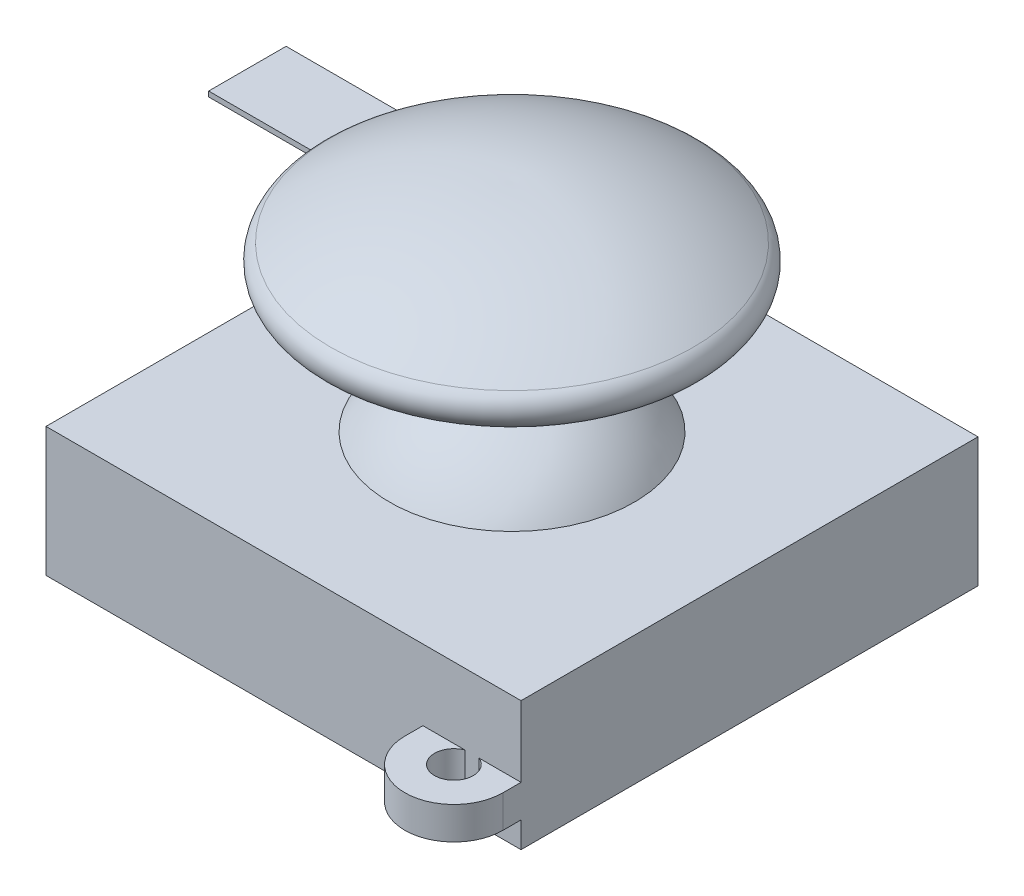
SolidWorks part; units mm, degrees
ref_plane "前视基准面" through (0, 0, 0) normal (0, 0, 1) x (1, 0, 0)
ref_plane "上视基准面" through (0, 0, 0) normal (0, 1, 0) x (1, 0, 0)
ref_plane "右视基准面" through (0, 0, 0) normal (1, 0, 0) x (0, 0, -1)
other "Configuration Table"
sketch "草图1" plane through (0, 0, 0) normal (0, 1, 0) x (1, 0, 0)
  line L1 (-9.2, -8.85) -> (9.2, -8.85)
  line L2 (-9.2, -8.85) -> (-9.2, 8.85)
  line L3 (-9.2, 8.85) -> (9.2, 8.85)
  line L4 (9.2, -8.85) -> (9.2, 8.85)
  line L5 (-9.2, -8.85) -> (9.2, 8.85) construction
  line L6 (-9.2, 8.85) -> (9.2, -8.85) construction
  point P0 (0, 0)
  dimension "D1" = 18.4
  dimension "D2" = 17.7
extrude "凸台-拉伸1" add sketch "草图1" along normal blind 5
ref_plane "基准面1" through (0, 1, 0) normal (0, -1, 0) x (-1, 0, 0)
sketch "草图2" plane through (0, 1, 0) normal (0, -1, 0) x (-1, 0, 0)
  line L0 (9.2, 8.85) -> (10.9, 8.85)
  line L1 (10.9, 5.05) -> (9.2, 5.05)
  line L2 (9.2, 8.85) -> (9.2, -8.85) construction
  line L3 (9.2, 5.05) -> (9.2, 8.85)
  line L4 (-9.2, -8.85) -> (-9.2, -9.55)
  line L5 (-5.4, -9.55) -> (-5.4, -8.85)
  line L6 (9.2, -8.85) -> (-9.2, -8.85) construction
  line L7 (-5.4, -8.85) -> (-7.0307, -8.85)
  line L8 (-14.0215, -11.45) -> (-1.3838, -11.45) construction
  line L9 (-9.2, 8.85) -> (9.2, 8.85) construction
  line L11 (12.8, 10.4378) -> (12.8, 1.7571) construction
  line L12 (-9.2, -8.85) -> (-9.2, 8.85) construction
  line L13 (-7.5693, -8.85) -> (-9.2, -8.85)
  arc A0 (10.9, 8.85) -> (10.9, 5.05) centre (10.9, 6.95) cw
  arc A1 (-9.2, -9.55) -> (-5.4, -9.55) centre (-7.3, -9.55) ccw
  arc A2 (-7.5693, -8.85) -> (-7.0307, -8.85) centre (-7.3, -9.55) ccw
  circle A3 centre (10.9, 6.95) radius 0.9
  dimension "D3" = 1.5
  dimension "D4" = 1.8
  dimension "D1" = 3.8
  dimension "D2" = 3.8
  dimension "D5" = 20.3
  dimension "D6" = 22
extrude "凸台-拉伸2" add sketch "草图2" against normal blind 1.26
ref_plane "基准面2" through (0, 0, 0) normal (1, 0, 0) x (0, 0, -1)
sketch "草图3" plane through (0, 0, 0) normal (1, 0, 0) x (0, 0, -1)
  line L0 (0, 0) -> (0, 7.6055) construction
  line L1 (4.74, 5) -> (0, 5)
  line L2 (-8.85, 5) -> (8.85, 5) construction
  line L3 (0, 7.6055) -> (0, 5)
  line L5 (6.6158, 10) -> (1.85, 10)
  line L6 (1.85, 10) -> (1.85, 7.2919)
  line L8 (0, 13.4) -> (0, 7.6055)
  line L9 (7.35, 14.4714) -> (7.35, 9.5201) construction
  line L10 (-4.6633, 13.4036) -> (3.8323, 13.4036) construction
  arc A0 (4.74, 5) -> (1.85, 7.2919) centre (0, 1.9912) ccw
  arc A1 (0, 13.4) -> (7.0268, 11.3425) centre (0.2946, 1.3781) cw
  arc A2 (7.0268, 11.3425) -> (6.6158, 10) centre (6.6158, 10.7342) cw
  dimension "D1" = 4.74
  dimension "D2" = 13.4
  dimension "D3" = 7.35
  dimension "D4" = 1.85
  dimension "D5" = 5
revolve "旋转1" add sketch "草图3" angle 360 about L8
ref_plane "基准面3" through (0, 0.2, 0) normal (0, -1, 0) x (-1, 0, 0)
sketch "草图4" plane through (0, 0.2, 0) normal (0, -1, 0) x (-1, 0, 0)
  line L0 (9.2, 8.85) -> (9.2, 9.2075)
  line L1 (10.1425, 10.15) -> (21.9, 10.15)
  line L2 (21.9, 10.15) -> (21.9, 13.15)
  line L3 (21.9, 13.15) -> (10.05, 13.15)
  line L4 (6.2, 9.3) -> (6.2, 8.85)
  line L5 (-9.2, 8.85) -> (9.2, 8.85) construction
  line L6 (6.2, 8.85) -> (9.2, 8.85)
  line L7 (9.2, -8.85) -> (-9.2, -8.85) construction
  arc A0 (9.2, 9.2075) -> (10.1425, 10.15) centre (10.1425, 9.2075) cw
  arc A1 (10.05, 13.15) -> (6.2, 9.3) centre (10.05, 9.3) ccw
  point P15 (10.3797, 8.9703)
  point P16 (10.1425, 9.2075)
  point P17 (0, 0)
  point P18 (10.05, 9.3887)
  dimension "D1" = 3
  dimension "D2" = 3
  dimension "D3" = 15.7
  dimension "D4" = 22
extrude "凸台-拉伸3" add sketch "草图4" against normal blind 0.2
